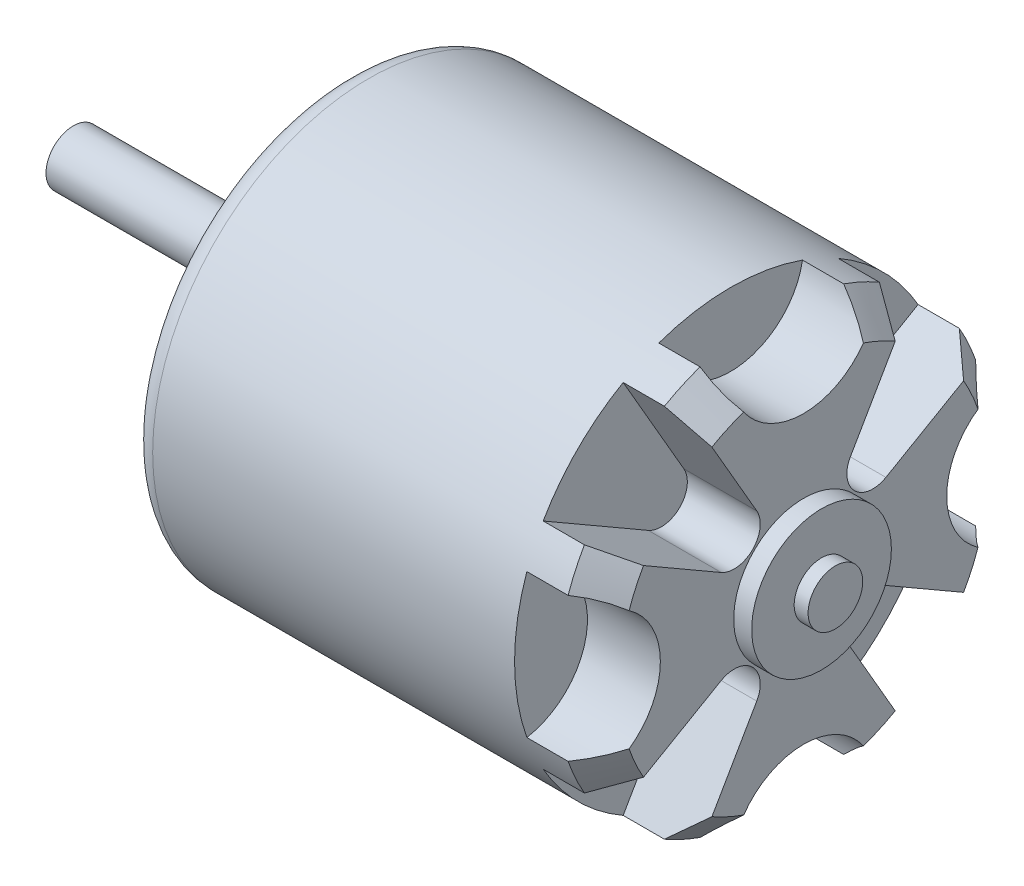
SolidWorks part; units mm, degrees
ref_plane "Front Plane" through (0, 0, 0) normal (0, 0, 1) x (1, 0, 0)
ref_plane "Top Plane" through (0, 0, 0) normal (0, 1, 0) x (1, 0, 0)
ref_plane "Right Plane" through (0, 0, 0) normal (1, 0, 0) x (0, 0, -1)
sketch "Sketch1" plane through (0, 0, 0) normal (1, 0, 0) x (0, 0, -1)
  circle A0 centre (0, 0) radius 31.623
  dimension "D1" = 63.246
extrude "Boss-Extrude1" add sketch "Sketch1" along normal blind 66.802
sketch "Sketch2" plane through (66.802, 0, 0) normal (1, 0, 0) x (0, 0, -1)
  line L0 (-31.623, 0) -> (31.623, 0) construction
  line L1 (0, 0) -> (-22.3608, 22.3608) construction
  line L2 (-12.0527, 6.8481) -> (-27.434, 15.7286)
  line L3 (-6.8481, 12.0527) -> (-15.7286, 27.434)
  line L4 (12.0527, 6.8481) -> (27.434, 15.7286)
  line L5 (6.8481, 12.0527) -> (15.7286, 27.434)
  line L6 (6.8481, -12.0527) -> (15.7286, -27.434)
  line L7 (12.0527, -6.8481) -> (27.434, -15.7286)
  line L8 (-12.0527, -6.8481) -> (-27.434, -15.7286)
  line L9 (-6.8481, -12.0527) -> (-15.7286, -27.434)
  arc A0 (-10.5151, 29.8236) -> (10.5151, 29.8236) centre (0, 31.623) ccw
  circle A1 centre (0, 0) radius 31.623 construction
  arc A2 (-29.8236, -10.5151) -> (-29.8236, 10.5151) centre (-31.623, 0) ccw
  arc A3 (29.8236, 10.5151) -> (29.8236, -10.5151) centre (31.623, 0) ccw
  arc A4 (10.5151, -29.8236) -> (-10.5151, -29.8236) centre (0, -31.623) ccw
  circle A5 centre (0, 0) radius 10.541
  arc A6 (-12.8418, 12.8418) -> (-6.8481, 12.0527) centre (-10.1477, 10.1477) ccw
  arc A7 (6.8481, 12.0527) -> (12.0527, 6.8481) centre (10.1477, 10.1477) ccw
  arc A8 (12.0527, -6.8481) -> (6.8481, -12.0527) centre (10.1477, -10.1477) ccw
  arc A9 (-6.8481, -12.0527) -> (-12.0527, -6.8481) centre (-10.1477, -10.1477) ccw
  circle A10 centre (0, 0) radius 31.623
  point P28 (0, 0)
  point P45 (0, 0)
  dimension "D1" = 21.336
  dimension "D2" = 21.336
  dimension "D3" = 21.336
  dimension "D4" = 21.336
  dimension "D8" = 21.082
  dimension "D10" = 7.62
  dimension "D5" = 31.623
  dimension "D6" = 31.623
  dimension "D7" = 31.623
  dimension "D9" = 45
  dimension "D12" = 15
  dimension "D13" = 30
  dimension "D11" = 4
  dimension "D14" = 4
extrude "Cut-Extrude1" cut sketch "Sketch2" against normal blind 10.668
chamfer "Chamfer1" distance 4.6355 angle 45 8 edges at (66.802, 28.7472, 13.1761) (66.802, 28.7472, -13.1761) (66.802, 13.1761, -28.7472) (66.802, -13.1761, -28.7472) (66.802, -28.7472, -13.1761) (66.802, -28.7472, 13.1761) (66.802, -13.1761, 28.7472) (66.802, 13.1761, 28.7472)
sketch "Sketch3" plane through (66.802, 0, 0) normal (1, 0, 0) x (0, 0, -1)
  circle A0 centre (0, 0) radius 10.2235
  dimension "D1" = 20.447
extrude "Boss-Extrude2" add sketch "Sketch3" along normal blind 2.6289
sketch "Sketch4" plane through (69.4309, 0, 0) normal (1, 0, 0) x (0, 0, -1)
  circle A0 centre (0, 0) radius 4
  dimension "D1" = 8
extrude "Boss-Extrude3" add sketch "Sketch4" along normal blind 2.032
sketch "Sketch5" plane through (0, 0, 0) normal (-1, 0, 0) x (0, 0, 1)
  circle A0 centre (0, 0) radius 8.7376
  dimension "D1" = 17.4752
extrude "Boss-Extrude4" add sketch "Sketch5" along normal blind 12.3698
sketch "Sketch6" plane through (-12.3698, 0, 0) normal (-1, 0, 0) x (0, 0, 1)
  circle A0 centre (0, 0) radius 4
  dimension "D1" = 8
extrude "Boss-Extrude5" add sketch "Sketch6" along normal blind 27.686
sketch "Sketch7" plane through (0, 0, 0) normal (-1, 0, 0) x (0, 0, 1)
  circle A0 centre (0, 0) radius 22.05
  dimension "D1" = 44.1
hole_wizard "M4x0.7 Tapped Hole1" positions "Sketch8" profile "Sketch9" tap size "M4x0.7" standard "ANSI Metric"
sketch "Sketch8" plane through (0, 0, 0) normal (-1, 0, 0) x (0, 0, 1)
  circle A0 centre (0, 0) radius 22.05 construction
  point P0 (0, 22.05)
  point P4 (-22.05, 0)
  point P6 (0, -22.05)
  point P8 (22.05, 0)
sketch "Sketch9" plane through (0, 22.05, 0) normal (0, 1, 0) x (0, 0, 1)
  line L0 (0, 0) -> (0, 10.8974)
  line L1 (0, 10.8974) -> (1.65, 9.906)
  line L2 (1.65, 9.906) -> (1.65, 0.375)
  line L3 (1.65, 0.375) -> (2.025, 0)
  line L5 (2.025, 0) -> (0, 0)
  line L6 (-1.65, 0.375) -> (-2.025, 0) construction
  line L10 (0, 10.8974) -> (-1.65, 9.906) construction
  line L11 (0, -6.35) -> (0, 107.95) construction
  dimension "Tap Drill Dia." = 3.3
  dimension "Tap Drill Depth" = 9.906
  dimension "Near C'Sink Dia." = 4.05
  dimension "Near C'Sink Angle" = 90
  dimension "Drill Angle" = 118
cosmetic thread "Hole Thread1" parameters "D1"=7.874, "D2"=4
cosmetic thread "Hole Thread2" parameters "D1"=7.874, "D2"=4
cosmetic thread "Hole Thread3" parameters "D1"=7.874, "D2"=4
cosmetic thread "Hole Thread4" parameters "D1"=7.874, "D2"=4
fillet "Fillet1" radius 3.175 1 edges at (0, 0, -31.623)
equation "\"D2@Sketch2\"=\"D1@Sketch2\""
equation "\"D3@Sketch2\"=\"D1@Sketch2\""
equation "\"D4@Sketch2\"=\"D1@Sketch2\""
equation "\"D13@Sketch2\"=\"D12@Sketch2\"*2"
